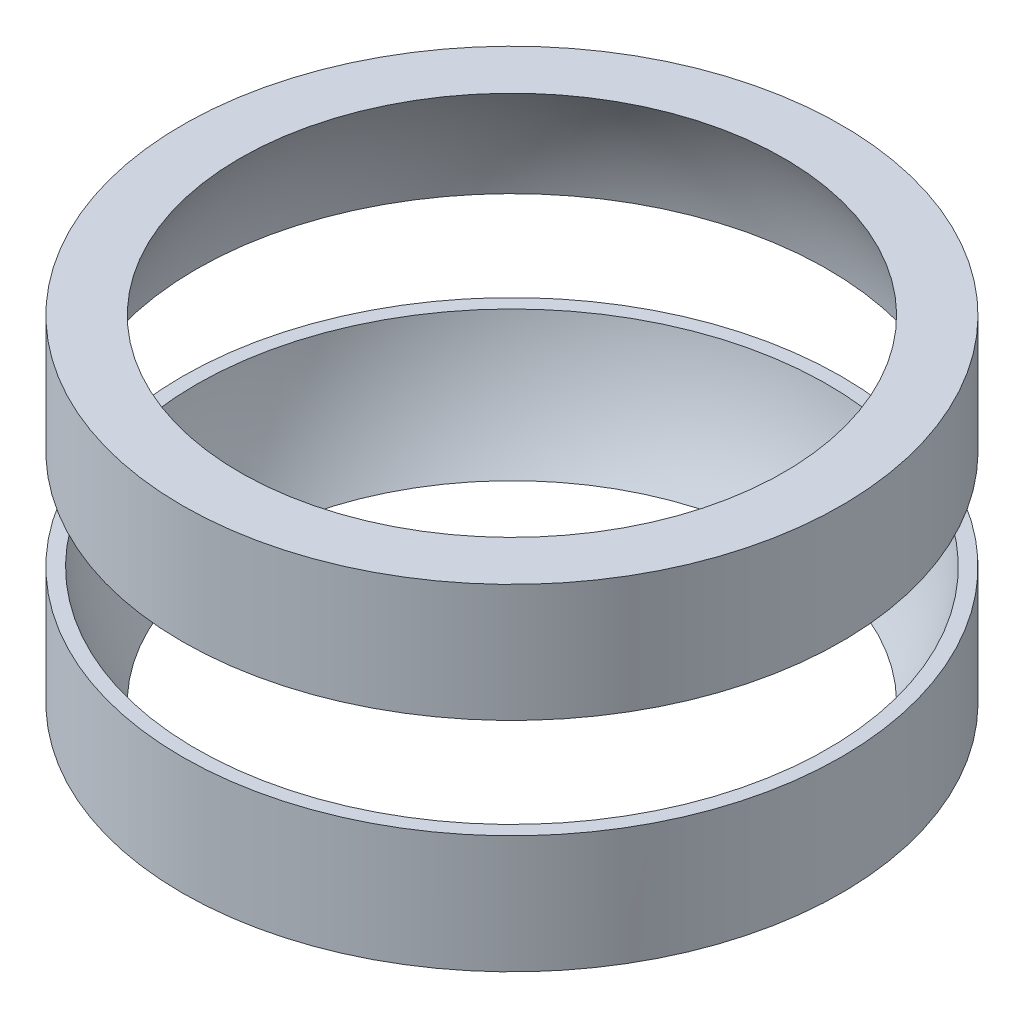
SolidWorks part; units mm, degrees
material "Brass"
ref_plane "Front Plane" through (0, 0, 0) normal (0, 0, 1) x (1, 0, 0)
ref_plane "Top Plane" through (0, 0, 0) normal (0, 1, 0) x (1, 0, 0)
ref_plane "Right Plane" through (0, 0, 0) normal (1, 0, 0) x (0, 0, -1)
sketch "Sketch2" plane through (0, 0, 0) normal (0, 0, 1) x (1, 0, 0)
  line L0 (-8.25, -4.2) -> (-8.25, 4.2)
  line L1 (-8.25, 4.2) -> (-6.8088, 4.2)
  line L3 (-6.8088, -4.2) -> (-8.25, -4.2)
  line L4 (-6.8088, 4.2) -> (0, 4.2) construction
  line L5 (0, 4.2) -> (0, -4.2) construction
  line L6 (0, -4.2) -> (-6.8088, -4.2) construction
  line L7 (-8, 0) -> (0, 0) construction
  arc A0 (-6.8088, 4.2) -> (-6.8088, -4.2) centre (0, 0) ccw
  dimension "D1" = 8.25
  dimension "D2" = 8
  dimension "D3" = 8.4
revolve "Revolve1" add sketch "Sketch2" angle 360 about L5
sketch "Sketch3" plane through (0, 0, 0) normal (0, 0, 1) x (1, 0, 0)
  line L0 (8.25, -4.2) -> (8.25, 4.2) construction
  line L1 (-8.25, -1.25) -> (8.25, -1.25)
  line L2 (-8.25, -1.25) -> (-8.25, 1.25)
  line L3 (-8.25, 1.25) -> (8.25, 1.25)
  line L4 (8.25, -1.25) -> (8.25, 1.25)
  line L5 (-8.25, -1.25) -> (8.25, 1.25) construction
  line L6 (-8.25, 1.25) -> (8.25, -1.25) construction
  point P0 (0, 0)
  dimension "D1" = 2.5
extrude "Cut-Extrude1" cut sketch "Sketch3" against normal through all both and the other way through all
